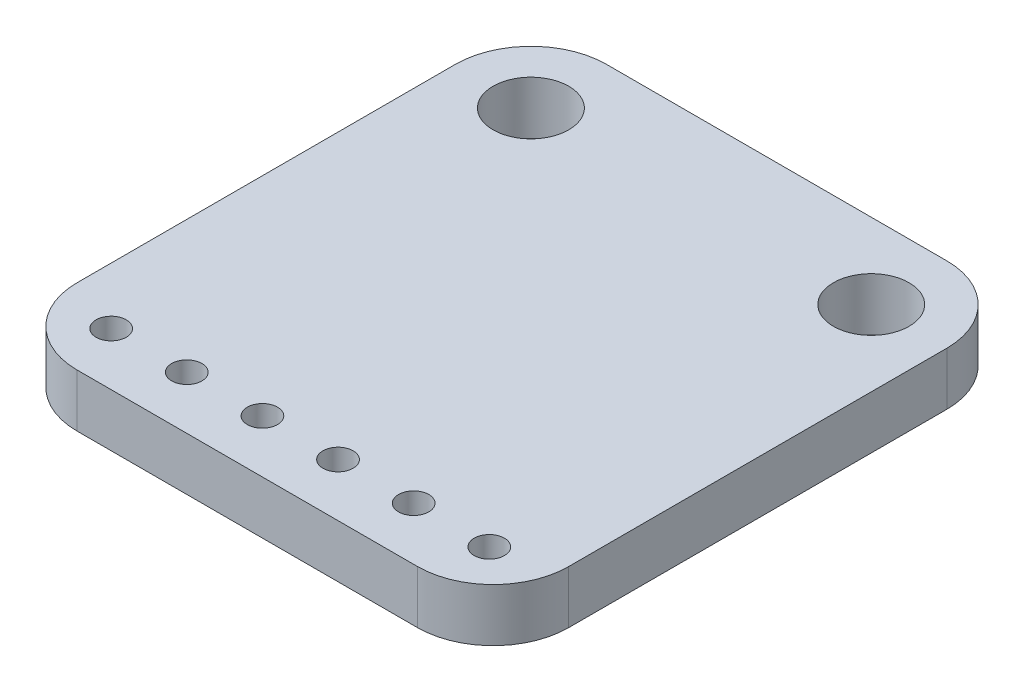
SolidWorks part; units mm, degrees
ref_plane "Front Plane" through (0, 0, 0) normal (0, 0, 1) x (1, 0, 0)
ref_plane "Top Plane" through (0, 0, 0) normal (0, 1, 0) x (1, 0, 0)
ref_plane "Right Plane" through (0, 0, 0) normal (1, 0, 0) x (0, 0, -1)
sketch "Sketch1" plane through (0, 0, 0) normal (0, 1, 0) x (1, 0, 0)
  line L1 (-8.255, 8.89) -> (8.255, 8.89)
  line L2 (-8.255, 8.89) -> (-8.255, -8.89)
  line L3 (-8.255, -8.89) -> (8.255, -8.89)
  line L4 (8.255, 8.89) -> (8.255, -8.89)
  line L5 (-8.255, 8.89) -> (8.255, -8.89) construction
  line L6 (-8.255, -8.89) -> (8.255, 8.89) construction
  point P0 (0, 0)
  dimension "D1" = 16.51
  dimension "D2" = 17.78
extrude "Boss-Extrude1" add sketch "Sketch1" along normal blind 1.778
fillet "Fillet1" radius 2.54 4 edges at (-8.255, 0.889, 8.89) (-8.255, 0.889, -8.89) (8.255, 0.889, -8.89) (8.255, 0.889, 8.89)
sketch "Sketch2" plane through (0, 1.778, 0) normal (0, 1, 0) x (1, 0, 0)
  line L0 (-8.255, -7.112) -> (8.255, -7.112) construction
  line L1 (-8.255, 6.35) -> (-8.255, -6.35) construction
  line L2 (8.255, -6.35) -> (8.255, 6.35) construction
  line L3 (-5.715, -8.89) -> (5.715, -8.89) construction
  circle A0 centre (-6.35, -7.112) radius 0.508
  circle A1 centre (-3.81, -7.112) radius 0.508
  circle A2 centre (-1.27, -7.112) radius 0.508
  circle A3 centre (1.27, -7.112) radius 0.508
  circle A4 centre (3.81, -7.112) radius 0.508
  circle A5 centre (6.35, -7.112) radius 0.508
  dimension "D3" = 1.016
  dimension "D1" = 1.778
  dimension "D2" = 1.905
  dimension "D5" = 1.905
  dimension "D4" = 6
extrude "Cut-Extrude1" cut sketch "Sketch2" against normal up to next
sketch "Sketch4" plane through (0, 0, 0) normal (0, -1, 0) x (-1, 0, 0)
  line L0 (12.1297, 1.27) -> (-13.0317, 1.27) construction
  line L1 (-1.975, 3.245) -> (1.975, 3.245)
  line L2 (-1.975, 3.245) -> (-1.975, -0.705)
  line L3 (-1.975, -0.705) -> (1.975, -0.705)
  line L4 (1.975, 3.245) -> (1.975, -0.705)
  line L5 (0, 10.9348) -> (0, -12.4719) construction
  line L6 (-8.255, -6.35) -> (-8.255, 6.35) construction
  line L7 (8.255, 6.35) -> (8.255, -6.35) construction
  line L8 (-5.715, 8.89) -> (5.715, 8.89) construction
  dimension "D1" = 3.95
  dimension "D2" = 3.95
  dimension "D3" = 7.62
extrude "Boss-Extrude3" add sketch "Sketch4" along normal blind 1.397
sketch "Sketch5" plane through (0, 0, 0) normal (0, -1, 0) x (-1, 0, 0)
  line L0 (-8.255, -6.35) -> (-8.255, 6.35) construction
  line L1 (-5.715, 8.89) -> (5.715, 8.89) construction
  line L2 (8.255, 6.35) -> (8.255, -6.35) construction
  circle A0 centre (-5.715, 6.35) radius 1.27
  circle A1 centre (5.715, 6.35) radius 1.27
  point P12 (5.5255, 8.89)
  dimension "D1" = 2.54
  dimension "D4" = 2.54
  dimension "D2" = 2.54
  dimension "D3" = 2.54
  dimension "D5" = 2.54
  dimension "D6" = 2.54
extrude "Cut-Extrude2" cut sketch "Sketch5" against normal up to next
